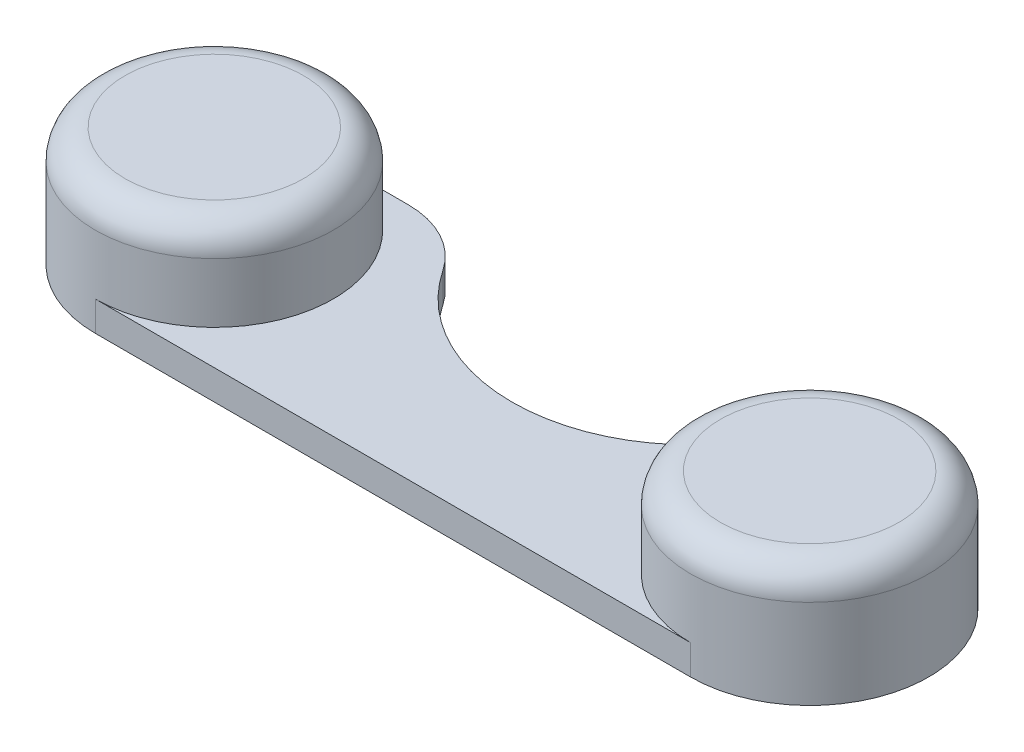
SolidWorks part; units mm, degrees
ref_plane "Front Plane" through (0, 0, 0) normal (0, 0, 1) x (1, 0, 0)
ref_plane "Top Plane" through (0, 0, 0) normal (0, 1, 0) x (1, 0, 0)
ref_plane "Right Plane" through (0, 0, 0) normal (1, 0, 0) x (0, 0, -1)
sketch "Sketch1" plane through (0, 0, 0) normal (0, 1, 0) x (1, 0, 0)
  circle A0 centre (0, 0) radius 4
  circle A1 centre (20, 0) radius 4
  dimension "D1" = 8
  dimension "D2" = 8
  dimension "D3" = 20
extrude "Boss-Extrude1" add sketch "Sketch1" along normal blind 4
fillet "Fillet1" radius 1 1 edges at (0, 4, 4)
fillet "Fillet2" radius 1 1 edges at (20, 4, 4)
sketch "Sketch2" plane through (0, 0, 0) normal (0, -1, 0) x (-1, 0, 0)
  line L5 (0, 4) -> (-20, 4)
  line L6 (0, 4) -> (0, -4)
  line L7 (0, -4) -> (-20, -4)
  line L8 (-20, 4) -> (-20, -4)
  circle A0 centre (0, 0) radius 4 construction
  circle A1 centre (-20, 0) radius 4 construction
extrude "Boss-Extrude2" add sketch "Sketch2" against normal blind 1
sketch "Sketch3" plane through (0, 1, 0) normal (0, 1, 0) x (1, 0, 0)
  circle A0 centre (10, 6) radius 6
  point P2 (0, 0)
  point P3 (0, 0)
  point P4 (0, 0)
extrude "Cut-Extrude1" cut sketch "Sketch3" against normal up to surface (1 mm away) contours A0 up to face at (10, 0, 0)
fillet "Fillet3" radius 3 2 edges at (4.3431, 0.5, -4) (15.6569, 0.5, -4)
